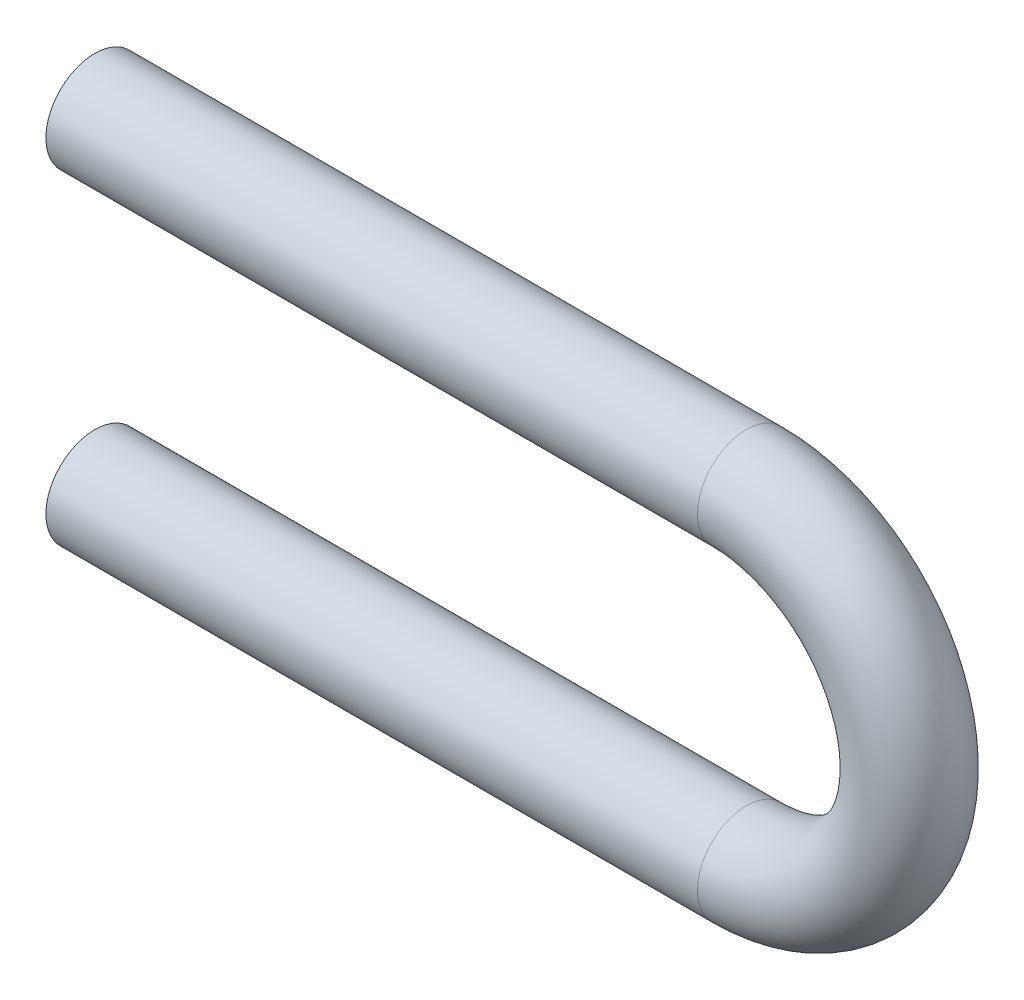
SolidWorks part; units mm, degrees
material "AISI 304"
ref_plane "Спереди" through (0, 0, 0) normal (0, 0, 1) x (1, 0, 0)
ref_plane "Сверху" through (0, 0, 0) normal (0, 1, 0) x (1, 0, 0)
ref_plane "Справа" through (0, 0, 0) normal (1, 0, 0) x (0, 0, -1)
sketch "Эскиз1" plane through (0, 0, 0) normal (0, 0, 1) x (1, 0, 0)
  line L0 (0, 0) -> (40, 0)
  line L1 (40, 20) -> (40, 0) construction
  line L2 (40, 20) -> (0, 20)
  arc A0 (40, 0) -> (40, 20) centre (40, 10) ccw
  dimension "D2" = 10
  dimension "D1" = 40
  dimension "D3" = 40
sketch "Эскиз2" plane through (0, 0, 0) normal (1, 0, 0) x (0, 0, -1)
  circle A0 centre (0, 0) radius 3
  dimension "D1" = 6
sweep "По траектории1" add profiles "Эскиз2" path "Эскиз1"
ref_plane "Плоскость1" through (0, 10, 0) normal (0, 1, 0) x (1, 0, 0)
sketch "Эскиз3" plane through (0, 10, 0) normal (0, 1, 0) x (1, 0, 0)
  line L0 (-14.3, 0) -> (14.3, 0) construction
  circle A0 centre (49.0532, 0) radius 10
  dimension "D1" = 20
ref_point "Точка2"
